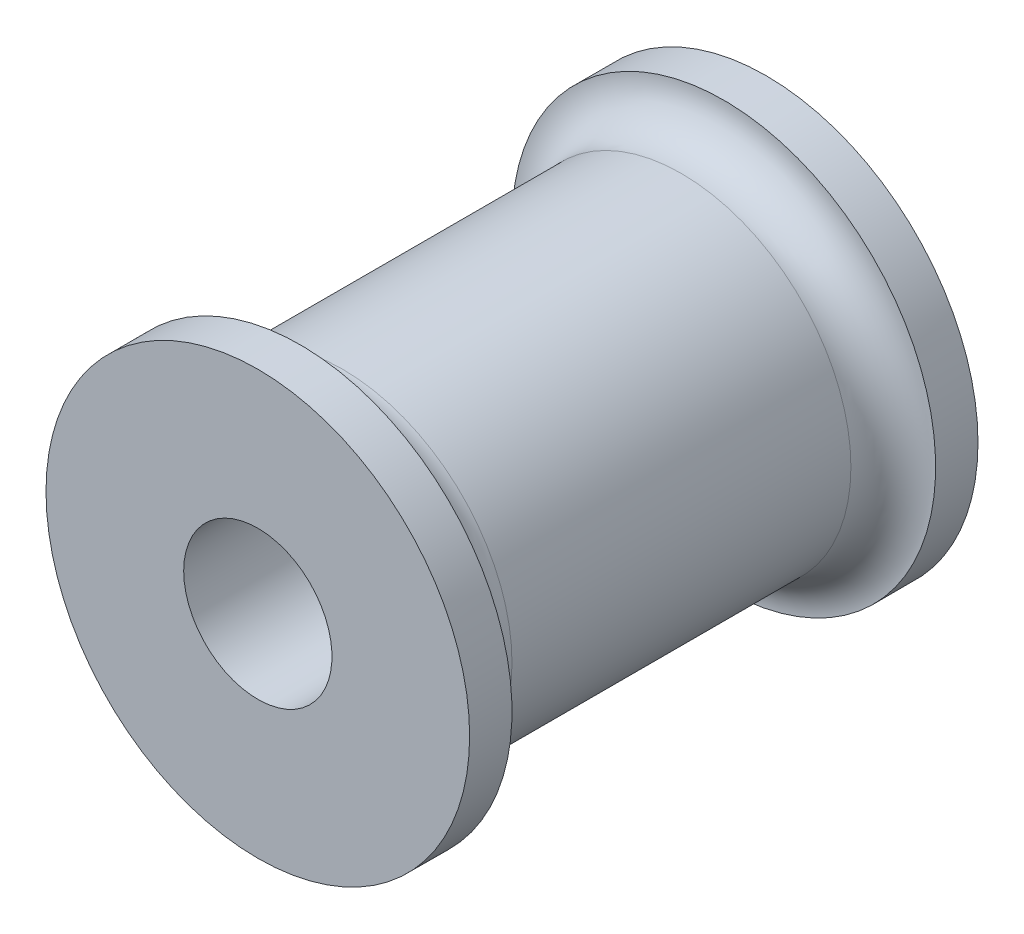
SolidWorks part; units mm, degrees
material "6061 Alloy"
ref_plane "Front Plane" through (0, 0, 0) normal (0, 0, 1) x (1, 0, 0)
ref_plane "Top Plane" through (0, 0, 0) normal (0, 1, 0) x (1, 0, 0)
ref_plane "Right Plane" through (0, 0, 0) normal (1, 0, 0) x (0, 0, -1)
sketch "Sketch1" plane through (0, 0, 0) normal (0, 0, 1) x (1, 0, 0)
  circle A0 centre (0, 0) radius 10
extrude "Boss-Extrude1" add sketch "Sketch1" along normal blind 24
sketch "Sketch2" plane through (0, 0, 0) normal (1, 0, 0) x (0, 0, -1)
  line L0 (0, 0) -> (0, 8.25) construction
  line L1 (0, -10) -> (0, 10) construction
  line L2 (-12, 10) -> (-12, 8.25) construction
  line L3 (0, 10) -> (-24, 10) construction
  line L4 (-12, 8.25) -> (0, 8.25) construction
  line L6 (-22, 10) -> (-2, 10)
  line L8 (-12, 10) -> (-12, 8) construction
  line L9 (-20, 8) -> (-4, 8)
  arc A1 (-2, 10) -> (-4, 8) centre (-4, 10) cw
  arc A2 (-22, 10) -> (-20, 8) centre (-20, 10) ccw
  point P11 (-12, 10)
  point P13 (-13.1626, 10)
  point P16 (-12, 8)
  dimension "D1" = 20
  dimension "D2" = 16
ref_axis "Axis1" through (0, 0, -0.3) along (0, 0, 1)
revolve "Cut-Revolve1" cut sketch "Sketch2" angle 360 about axis through (0, 0, -0.3) along (0, 0, 1)
sketch "Sketch3" plane through (0, 0, 0) normal (0, 0, -1) x (-1, 0, 0)
  circle A0 centre (0, 0) radius 3.5
extrude "Cut-Extrude1" cut sketch "Sketch3" against normal blind 24
